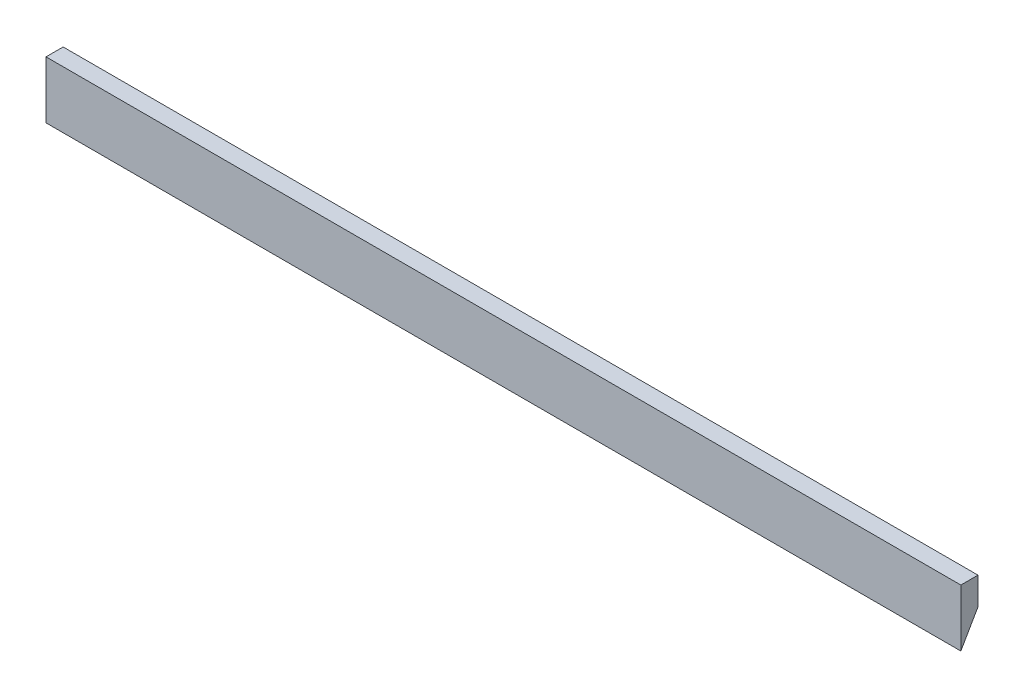
SolidWorks part; units mm, degrees
material "Acrílico (Impacto medio-alto)"
ref_plane "Alzado" through (0, 0, 0) normal (0, 0, 1) x (1, 0, 0)
ref_plane "Planta" through (0, 0, 0) normal (0, 1, 0) x (1, 0, 0)
ref_plane "Vista lateral" through (0, 0, 0) normal (1, 0, 0) x (0, 0, -1)
sketch "Croquis1" plane through (0, 0, 0) normal (0, 0, 1) x (1, 0, 0)
  line L1 (-80, 5) -> (80, 5)
  line L2 (-80, 5) -> (-80, -5)
  line L3 (-80, -5) -> (80, -5)
  line L4 (80, 5) -> (80, -5)
  line L5 (-80, 5) -> (80, -5) construction
  line L6 (-80, -5) -> (80, 5) construction
  point P0 (0, 0)
  dimension "D1" = 160
  dimension "D2" = 10
extrude "Saliente-Extruir1" add sketch "Croquis1" along normal blind 3
sketch "Croquis2" plane through (-80, 0, 0) normal (-1, 0, 0) x (0, 0, 1)
  line L0 (3, -5) -> (0, 0.1962)
  line L1 (0, 5) -> (0, -5) construction
  line L3 (0, 5) -> (3, 5)
  line L4 (0, 5) -> (0, -5)
  line L5 (0, -5) -> (3, -5)
  line L6 (3, 5) -> (3, -5)
  line M2 (0, 5) -> (0, -5)
  line M3 (0, -5) -> (3, -5)
  dimension "D1" = 150
extrude "Cortar-Extruir1" cut sketch "Croquis2" against normal through all contours L0 M3 M2
